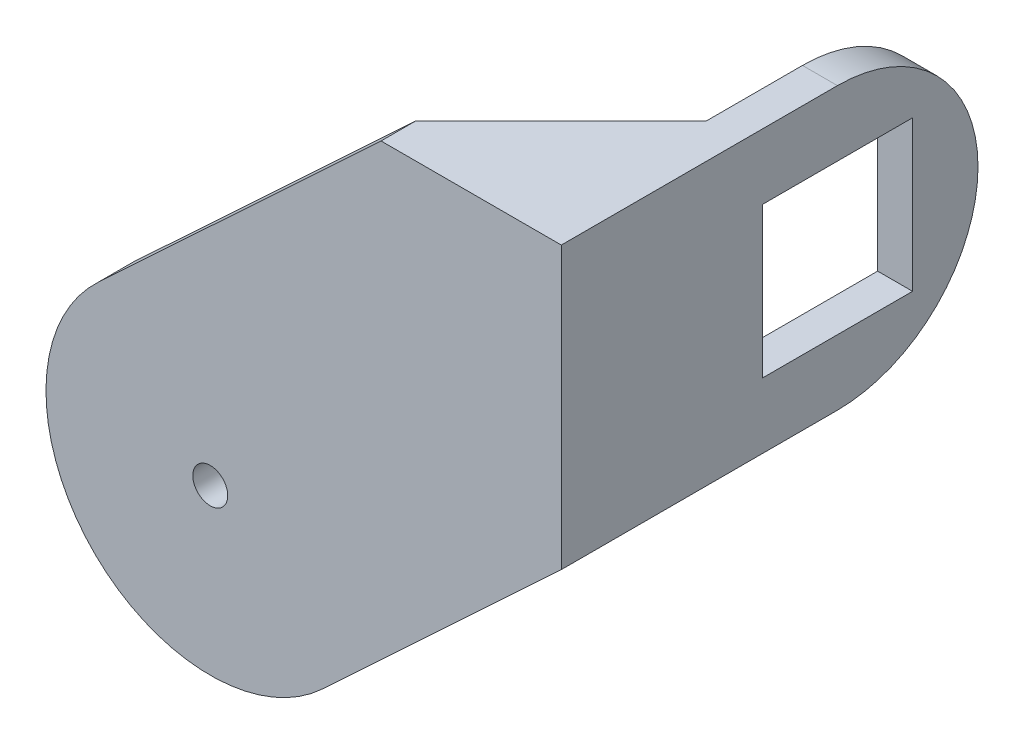
SolidWorks part; units mm, degrees
ref_plane "Front Plane" through (0, 0, 0) normal (0, 0, 1) x (1, 0, 0)
ref_plane "Top Plane" through (0, 0, 0) normal (0, 1, 0) x (1, 0, 0)
ref_plane "Right Plane" through (0, 0, 0) normal (1, 0, 0) x (0, 0, -1)
sketch "Sketch2" plane through (0, 0, 0) normal (0, 0, 1) x (1, 0, 0)
  line L0 (170.2049, 365.9774) -> (860.2049, 365.9774) construction
  line L1 (714.8857, 86.3037) -> (714.8857, 745.3037) construction
  line L2 (773.2149, 639.4787) -> (841.5963, 703.2454)
  line L3 (841.5963, 703.2454) -> (841.5963, 783.6782)
  line L4 (841.5963, 783.6782) -> (790.0196, 783.6782)
  line L5 (790.0196, 783.6782) -> (709.107, 708.226)
  arc A0 (709.107, 708.226) -> (773.2149, 639.4787) centre (741.1609, 673.8523) ccw
  circle A1 centre (741.1609, 673.8523) radius 5
  dimension "D2" = 47
  dimension "D4" = 10
  dimension "D1" = 659
  dimension "D3" = 137
extrude "Boss-Extrude1" add sketch "Sketch2" along normal blind 10 contours L5 A0 L2 L3 L4 A1
sketch "Sketch5" plane through (841.5963, 0, 0) normal (1, 0, 0) x (0, 0, -1)
  line L0 (0, 783.6782) -> (69, 783.6782)
  line L1 (69, 703.2454) -> (0, 703.2454)
  line L2 (0, 703.2454) -> (0, 783.6782)
  line L3 (320.6048, -69.4867) -> (320.5035, 589.5133) construction
  line L4 (0, 703.2454) -> (0, 783.6782)
  line L5 (0, 783.6782) -> (-10, 783.6782)
  line L6 (0, 703.2454) -> (0, 783.6782)
  line L7 (-10, 703.2454) -> (0, 703.2454)
  line L9 (0, 783.6782) -> (-10, 783.6782)
  line L11 (-10, 703.2454) -> (0, 703.2454)
  line L12 (47.5, 764.9618) -> (90.5, 721.9618) construction
  line L13 (47.5, 764.9618) -> (90.5, 764.9618)
  line L14 (47.5, 764.9618) -> (47.5, 721.9618)
  line L15 (47.5, 721.9618) -> (90.5, 721.9618)
  line L16 (90.5, 764.9618) -> (90.5, 721.9618)
  line L17 (90.5, 764.9618) -> (47.5, 721.9618) construction
  line L22 (-10, 783.6782) -> (-10, 703.2454)
  line L23 (-10, 783.6782) -> (-10, 703.2454)
  arc A0 (69, 783.6782) -> (69, 703.2454) centre (69, 743.4618) cw
  point P7 (0, 0)
  dimension "D2" = 659
  dimension "D3" = 69
  dimension "D4" = 43
  dimension "D1" = 0
extrude "Boss-Extrude3" add sketch "Sketch5" against normal blind 10
sketch "Sketch6" plane through (0, 783.6782, 0) normal (0, 1, 0) x (1, 0, 0)
  line L0 (790.0196, 0) -> (831.5963, 41.5766)
  line L1 (831.5963, 0) -> (831.5963, 69) construction
  line L2 (831.5963, 0) -> (790.0196, 0) construction
  line L3 (831.5963, 0) -> (790.0196, 0)
  line L4 (831.5963, 0) -> (831.5963, 41.5766)
  dimension "D1" = 45
extrude "Boss-Extrude4" add sketch "Sketch6" against normal blind 10
ref_plane "Plane1" through (0, 743.4618, 0) normal (0, 1, 0) x (1, 0, 0)
mirror "Mirror1" about plane through (0, 743.4618, 0) normal (0, 1, 0) of "Boss-Extrude4"
